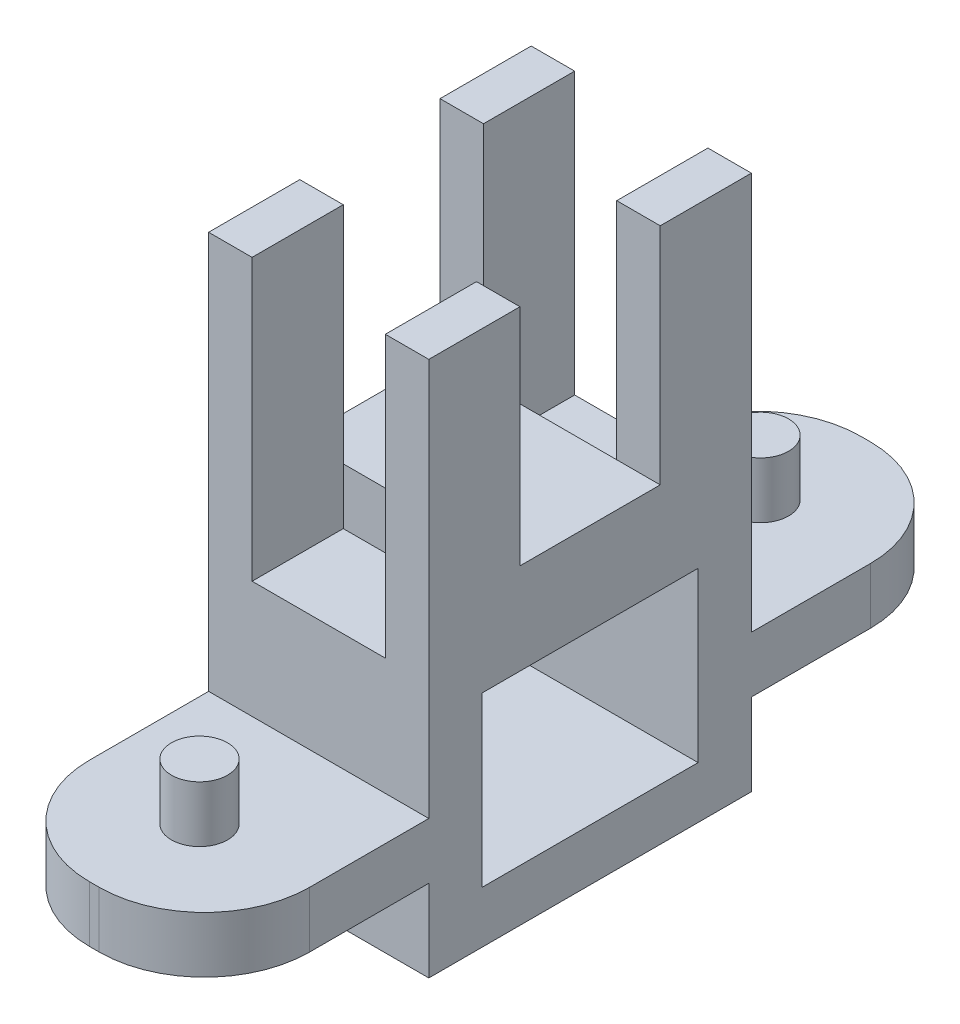
SolidWorks part; units mm, degrees
ref_plane "Front Plane" through (0, 0, 0) normal (0, 0, 1) x (1, 0, 0)
ref_plane "Top Plane" through (0, 0, 0) normal (0, 1, 0) x (1, 0, 0)
ref_plane "Right Plane" through (0, 0, 0) normal (1, 0, 0) x (0, 0, -1)
sketch "Sketch4" plane through (0, 0, 0) normal (0, 0, 1) x (1, 0, 0)
  line L0 (0, 82.063) -> (0, -112.4411) construction
  line L1 (-144.2959, 0) -> (145.5617, 0) construction
  line L2 (-12.7, 12.7) -> (-12.7, -12.7)
  line L3 (-15.7, 15.7) -> (15.7, 15.7)
  line L4 (-15.7, 15.7) -> (-15.7, -15.7)
  line L5 (-15.7, -15.7) -> (15.7, -15.7)
  line L6 (15.7, 15.7) -> (15.7, -15.7)
  line L7 (-12.7, -12.7) -> (12.7, -12.7)
  line L8 (12.7, 12.7) -> (12.7, -12.7)
  line L9 (-12.7, 12.7) -> (12.7, 12.7)
  dimension "D2" = 12.7
  dimension "D3" = 12.7
  dimension "D4" = 12.7
  dimension "D5" = 12.7
  dimension "D1" = 3
extrude "Boss-Extrude3" add sketch "Sketch4" along normal blind 30
sketch "Sketch5" plane through (0, 0, 30) normal (0, 0, 1) x (1, 0, 0)
  line L0 (-15.7, 15.7) -> (15.7, 15.7)
  line L1 (15.7, 15.7) -> (15.7, -15.7)
  line L2 (15.7, -15.7) -> (-15.7, -15.7)
  line L3 (-15.7, -15.7) -> (-15.7, 15.7)
extrude "Boss-Extrude4" add sketch "Sketch5" along normal blind 5
sketch "Sketch6" plane through (0, 0, 35) normal (0, 0, 1) x (1, 0, 0)
  line L0 (-14.6567, 0) -> (15.7, 0) construction
  line L1 (15.7, -15.7) -> (15.7, 15.7) construction
  line L2 (-15.7, 4) -> (15.7, 4)
  line L3 (-15.7, 15.7) -> (-15.7, -15.7) construction
  line L4 (15.7, 4) -> (15.7, -4)
  line L5 (15.7, -4) -> (-15.7, -4)
  line L6 (-15.7, -4) -> (-15.7, 4)
  dimension "D1" = 4
  dimension "D2" = 4
extrude "Boss-Extrude5" add sketch "Sketch6" along normal blind 5
sketch "Sketch7" plane through (0, -4, 0) normal (0, -1, 0) x (1, 0, 0)
  line L0 (-15.7, 40) -> (-15.7, 52)
  line L1 (-0.7, 67) -> (0.7, 67)
  line L2 (15.7, 52) -> (15.7, 40)
  line L3 (-15.7, 40) -> (15.7, 40) construction
  line L4 (15.7, 40) -> (-15.7, 40)
  line L5 (0, 0) -> (0, 92.3619) construction
  arc A0 (0.7, 67) -> (15.7, 52) centre (0.7, 52) cw
  arc A1 (-15.7, 52) -> (-0.7, 67) centre (-0.7, 52) cw
  point P9 (15.7, 67)
  point P12 (-15.7, 67)
  dimension "D3" = 15
  dimension "D1" = 27
  dimension "D2" = 31.4
extrude "Boss-Extrude6" add sketch "Sketch7" against normal blind 8
sketch "Sketch8" plane through (0, -4, 0) normal (0, -1, 0) x (1, 0, 0)
  line L0 (0, 67.4318) -> (0, -5.9603) construction
  line L1 (0.7, 67) -> (-0.7, 67) construction
  circle A0 centre (0, 52) radius 4
  dimension "D1" = 15
extrude "Boss-Extrude7" add sketch "Sketch8" along normal blind 8
mirror "Mirror1" about plane through (0, 0, 0) normal (0, 1, 0) of "Boss-Extrude7"
sketch "Sketch9" plane through (0, 15.7, 0) normal (0, 1, 0) x (1, 0, 0)
  line L1 (-15.7, -32) -> (15.7, -32)
  line L2 (-15.7, -35) -> (-15.7, 0) construction
  line L3 (15.7, -35) -> (15.7, 0) construction
  line L4 (0, 15.8647) -> (0, -78.6922) construction
  line L5 (0, -52) -> (31.7707, -52) construction
  line L6 (31.7707, -52) -> (-30.9902, -52) construction
  line L7 (-15.7, -32) -> (-15.7, -22)
  line L8 (-15.7, -22) -> (15.7, -22)
  line L9 (15.7, -22) -> (15.7, -32)
  dimension "D1" = 20
  dimension "D2" = 10
extrude "Boss-Extrude8" add sketch "Sketch9" along normal blind 5
sketch "Sketch10" plane through (0, 15.7, 0) normal (0, 1, 0) x (1, 0, 0)
  line L0 (-15.7, -22) -> (-15.7, -12)
  line L1 (-15.7, -22) -> (-15.7, 0) construction
  line L2 (-15.7, -12) -> (15.7, -12)
  line L3 (15.7, -22) -> (15.7, 0) construction
  line L4 (15.7, -12) -> (15.7, -22)
  line L5 (15.7, -22) -> (-15.7, -22)
  dimension "D1" = 10
extrude "Boss-Extrude9" add sketch "Sketch10" along normal blind 13
sketch "Sketch11" plane through (0, 20.7, 0) normal (0, 1, 0) x (1, 0, 0)
  line L0 (-15.7, -22) -> (-9.5, -22)
  line L1 (15.7, -22) -> (-15.7, -22) construction
  line L2 (-9.5, -22) -> (-9.5, -32)
  line L3 (-15.7, -32) -> (15.7, -32) construction
  line L4 (-9.5, -32) -> (-15.7, -32)
  line L5 (-15.7, -32) -> (-15.7, -22)
  line L6 (9.5, -22) -> (9.5, -32)
  line L7 (-15.7, -22) -> (15.7, -22) construction
  line L8 (-15.7, -32) -> (15.7, -32) construction
  line L9 (9.5, -32) -> (15.7, -32)
  line L10 (15.7, -32) -> (15.7, -22)
  line L11 (15.7, -32) -> (15.7, -22) construction
  line L12 (15.7, -22) -> (9.5, -22)
  dimension "D1" = 6.2
  dimension "D2" = 6.2
extrude "Boss-Extrude10" add sketch "Sketch11" along normal blind 40
sketch "Sketch12" plane through (0, 0, 32) normal (0, 0, 1) x (1, 0, 0)
  line L0 (-15.7, 60.7) -> (-9.5, 60.7)
  line L1 (-9.5, 60.7) -> (-9.5, 20.7)
  line L2 (-9.5, 20.7) -> (9.5, 20.7)
  line L3 (9.5, 20.7) -> (9.5, 60.7)
  line L4 (9.5, 60.7) -> (15.7, 60.7)
  line L5 (15.7, 60.7) -> (15.7, 15.7)
  line L6 (15.7, 15.7) -> (-15.7, 15.7)
  line L7 (-15.7, 15.7) -> (-15.7, 60.7)
extrude "Boss-Extrude11" add sketch "Sketch12" along normal blind 3
sketch "Sketch13" plane through (-15.7, 0, 0) normal (-1, 0, 0) x (0, 0, 1)
  line L0 (35, -15.7) -> (0, -15.7) construction
  line L1 (0, 15.7) -> (31.4, 15.7)
  line L2 (0, 15.7) -> (0, -15.7)
  line L3 (0, -15.7) -> (31.4, -15.7)
  line L4 (31.4, 15.7) -> (31.4, -15.7)
  dimension "D1" = 31.4
extrude "Cut-Extrude1" cut sketch "Sketch13" against normal blind 31.4
sketch "Sketch14" plane through (0, 0, 31.4) normal (0, 0, -1) x (-1, 0, 0)
  line L0 (-15.7, 15.7) -> (15.7, 15.7)
  line L1 (15.7, 15.7) -> (15.7, -15.7)
  line L2 (15.7, -15.7) -> (-15.7, -15.7)
  line L3 (-15.7, -15.7) -> (-15.7, 15.7)
extrude "Boss-Extrude12" add sketch "Sketch14" along normal blind 4
sketch "Sketch16" plane through (0, 0, 27.4) normal (0, 0, -1) x (-1, 0, 0)
  line L0 (-15.7, 15.7) -> (-15.7, -15.7) construction
  line L1 (-15.7, -7.7) -> (15.7, -7.7)
  line L2 (-15.7, -7.7) -> (-15.7, -15.7)
  line L3 (-15.7, -15.7) -> (15.7, -15.7)
  line L4 (15.7, -7.7) -> (15.7, -15.7)
  line L5 (15.7, -15.7) -> (15.7, 15.7) construction
  dimension "D1" = 8
extrude "Boss-Extrude13" add sketch "Sketch16" along normal blind 15.4
mirror "Mirror2" about plane through (-15.7, 28.7, 12) normal (0, 0, 1) of "Boss-Extrude5", "Boss-Extrude3", "Boss-Extrude4", "Boss-Extrude6", "Boss-Extrude8", "Boss-Extrude7", "Mirror1", "Boss-Extrude9", "Boss-Extrude10", "Boss-Extrude11", "Boss-Extrude12", "Boss-Extrude13"
sketch "Sketch17" plane through (-15.7, 0, 0) normal (-1, 0, 0) x (0, 0, 1)
  line L0 (35, 60.7) -> (35, 4) construction
  line L1 (27.4, 15.7) -> (-3.4, 15.7)
  line L2 (27.4, 15.7) -> (27.4, -8.3)
  line L3 (27.4, -8.3) -> (-3.4, -8.3)
  line L4 (-3.4, 15.7) -> (-3.4, -8.3)
  line L5 (-11, 60.7) -> (-11, 4) construction
  line L6 (35, -15.7) -> (-11, -15.7) construction
  dimension "D1" = 7.6
  dimension "D2" = 7.6
  dimension "D3" = 30.8
  dimension "D4" = 24
  dimension "D5" = 7.4
extrude "Cut-Extrude2" cut sketch "Sketch17" against normal blind 31.4
